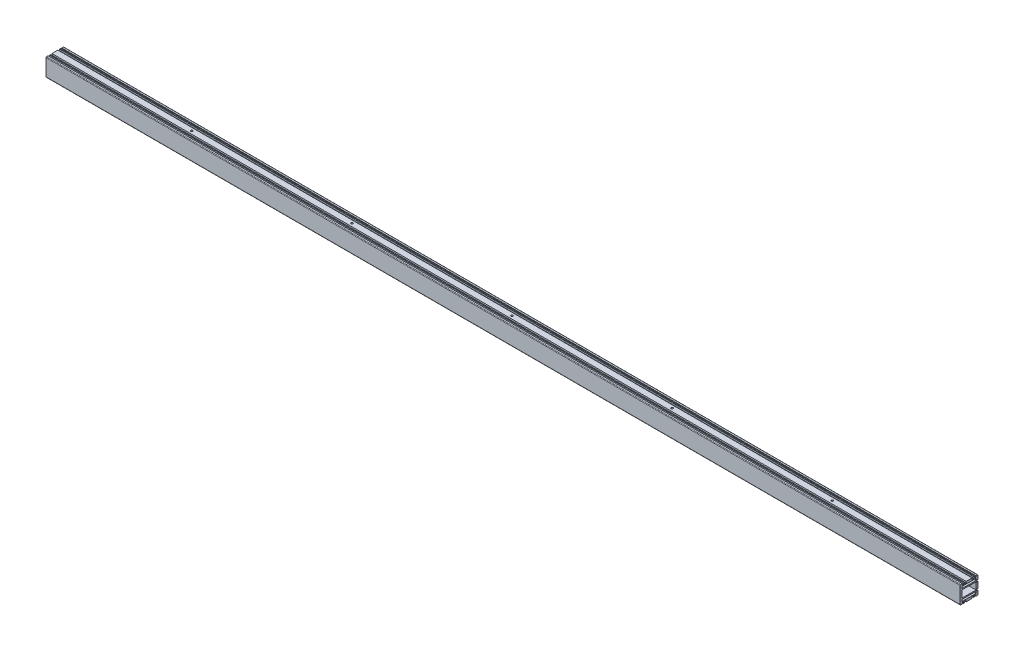
SolidWorks part; units mm, degrees
ref_plane "前视基准面" through (0, 0, 0) normal (0, 0, 1) x (1, 0, 0)
ref_plane "上视基准面" through (0, 0, 0) normal (0, 1, 0) x (1, 0, 0)
ref_plane "右视基准面" through (0, 0, 0) normal (1, 0, 0) x (0, 0, -1)
sketch "草图1" plane through (0, 0, 0) normal (1, 0, 0) x (0, 0, -1)
  line L0 (-15, 15) -> (15, -15) construction
  line L1 (-14, 15) -> (-11.5, 15)
  line L2 (-15, 14) -> (-15, -14)
  line L3 (-14, -15) -> (-11.5, -15)
  line L4 (15, 14) -> (15, 8)
  line L5 (15, 15) -> (-15, -15) construction
  line L6 (-11.5, 15) -> (-11.5, 13.5)
  line L7 (-11.5, 13.5) -> (-11.4, 13.5)
  line L8 (-11, 13.1) -> (-11, 12)
  line L9 (-11, 12) -> (-9.5, 12)
  line L10 (-9.5, 12) -> (-9.5, 15)
  line L11 (-9.5, 15) -> (-8, 15)
  line L12 (-8, 15) -> (-8, 12.5)
  line L13 (-8, 12.5) -> (-5, 12.5)
  line L14 (-5, 12.5) -> (-5, 15)
  line L15 (-5, 15) -> (5, 15)
  line L16 (0, 21.5201) -> (0, -18.309) construction
  line L17 (0, 55) -> (0, -55) construction
  line L18 (5, 12.5) -> (5, 15)
  line L19 (8, 12.5) -> (5, 12.5)
  line L20 (8, 15) -> (8, 12.5)
  line L21 (9.5, 15) -> (8, 15)
  line L22 (9.5, 12) -> (9.5, 15)
  line L23 (11, 12) -> (9.5, 12)
  line L24 (11, 13.1) -> (11, 12)
  line L25 (11.5, 13.5) -> (11.4, 13.5)
  line L26 (11.5, 15) -> (11.5, 13.5)
  line L27 (8, 15) -> (9.5, 15)
  line L28 (11.5, 15) -> (14, 15)
  line L29 (-19.8303, 0) -> (22.13, 0) construction
  line L30 (55, 0) -> (-55, 0) construction
  line L31 (8, -15) -> (9.5, -15)
  line L32 (11.5, -15) -> (11.5, -13.5)
  line L33 (11.5, -13.5) -> (11.4, -13.5)
  line L34 (11, -13.1) -> (11, -12)
  line L35 (11, -12) -> (9.5, -12)
  line L36 (9.5, -12) -> (9.5, -15)
  line L37 (9.5, -15) -> (8, -15)
  line L38 (8, -15) -> (8, -12.5)
  line L39 (8, -12.5) -> (5, -12.5)
  line L40 (5, -12.5) -> (5, -15)
  line L41 (-5, -15) -> (5, -15)
  line L42 (-5, -12.5) -> (-5, -15)
  line L43 (-8, -12.5) -> (-5, -12.5)
  line L44 (-8, -15) -> (-8, -12.5)
  line L45 (-9.5, -15) -> (-8, -15)
  line L46 (-9.5, -12) -> (-9.5, -15)
  line L47 (-11, -12) -> (-9.5, -12)
  line L48 (-11, -13.1) -> (-11, -12)
  line L49 (-11.5, -13.5) -> (-11.4, -13.5)
  line L50 (-11.5, -15) -> (-11.5, -13.5)
  line L51 (-9.5, -15) -> (-8, -15)
  line L52 (-5, -15) -> (5, -15)
  line L53 (8, -15) -> (9.5, -15)
  line L54 (11.5, -15) -> (14, -15)
  line L55 (15, 8) -> (12.5, 8)
  line L56 (12.5, 8) -> (12.5, 5)
  line L57 (12.5, 5) -> (15, 5)
  line L58 (12.5, -5) -> (15, -5)
  line L59 (12.5, -8) -> (12.5, -5)
  line L60 (15, -8) -> (12.5, -8)
  line L61 (15, 5) -> (15, -5)
  line L62 (15, -8) -> (15, -14)
  line L63 (12, -10.5) -> (12, -8.5)
  line L64 (-11.5, 11) -> (11.5, 11)
  line L65 (-12, 10.5) -> (-12, 8.5)
  line L66 (-11.5, 8) -> (11.5, 8)
  line L67 (12, 10.5) -> (12, 8.5)
  line L68 (-11.5, -8) -> (11.5, -8)
  line L69 (-12, -10.5) -> (-12, -8.5)
  line L70 (-11.5, -11) -> (11.5, -11)
  line L72 (-11.75, 6) -> (11.75, 6)
  line L73 (-11.75, 6) -> (-11.75, -6)
  line L74 (-11.75, -6) -> (11.75, -6)
  line L75 (11.75, 6) -> (11.75, -6)
  arc A0 (12, 8.5) -> (11.5, 8) centre (11.5, 8.5) cw
  arc A1 (11.5, 11) -> (12, 10.5) centre (11.5, 10.5) cw
  arc A2 (-11.5, 11) -> (-12, 10.5) centre (-11.5, 10.5) ccw
  arc A3 (-11.5, 8) -> (-12, 8.5) centre (-11.5, 8.5) cw
  arc A4 (-11, -13.1) -> (-11.4, -13.5) centre (-11.4, -13.1) cw
  arc A5 (11.4, -13.5) -> (11, -13.1) centre (11.4, -13.1) cw
  arc A6 (11.4, 13.5) -> (11, 13.1) centre (11.4, 13.1) ccw
  arc A7 (-11, 13.1) -> (-11.4, 13.5) centre (-11.4, 13.1) ccw
  arc A8 (-11.5, -8) -> (-12, -8.5) centre (-11.5, -8.5) ccw
  arc A9 (-11.5, -11) -> (-12, -10.5) centre (-11.5, -10.5) cw
  arc A10 (11.5, -11) -> (12, -10.5) centre (11.5, -10.5) ccw
  arc A11 (12, -8.5) -> (11.5, -8) centre (11.5, -8.5) ccw
  arc A12 (14, 15) -> (15, 14) centre (14, 14) cw
  arc A13 (14, -15) -> (15, -14) centre (14, -14) ccw
  arc A14 (-15, -14) -> (-14, -15) centre (-14, -14) ccw
  arc A15 (-15, 14) -> (-14, 15) centre (-14, 14) cw
  point P69 (12, 11)
  point P72 (-12, 11)
  point P77 (-11, -13.5)
  point P80 (11, -13.5)
  point P83 (11, 13.5)
  point P86 (-11, 13.5)
  point P99 (-12, -11)
  point P100 (12, -11)
  dimension "D17" = 0.5
  dimension "D18" = 0.4
  dimension "D21" = 1
  dimension "D1" = 3.5
  dimension "D2" = 1.5
  dimension "D3" = 0.5
  dimension "D4" = 1.5
  dimension "D5" = 3
  dimension "D6" = 30
  dimension "D7" = 30
  dimension "D8" = 1.5
  dimension "D9" = 2.5
  dimension "D10" = 3
  dimension "D11" = 2.5
  dimension "D12" = 7
  dimension "D13" = 3
  dimension "D14" = 4
  dimension "D15" = 3
  dimension "D16" = 24
  dimension "D19" = 23.5
  dimension "D20" = 12
extrude "凸台-拉伸1" add sketch "草图1" along normal mid plane 1542 contours A15 L2 A14 L3 L50 L49 A4 L48 L47 L46 L45 L44 L43 L42 L41 L40 L39 L38 L31 L36 L35 L34 A5 L33 L32 L54 A13 L62 L60 L59 L58 L61 L57 L56 L55 L4 A12 L28 L26 L25 A6 L24 L23 L22 L21 L20 L19 L18 L15 L14 L13
hole_wizard "M6 螺纹孔1" positions "草图3" profile "草图2" tap size "M6" standard "GB"
sketch "草图3" plane through (0, -15, 0) normal (0, -1, 0) x (1, 0, 0)
  line L0 (-771, -11.5) -> (-771, -14) construction
  line L1 (771, -15) -> (-771, -15) construction
  point P0 (-751, 0)
  point P1 (-736, 0)
  point P4 (736, 0)
  point P7 (751, 0)
  dimension "D1" = 20
  dimension "D2" = 15
sketch "草图2" plane through (-751, -15, 0) normal (1, 0, 0) x (0, 0, -1)
  line L0 (0, 0) -> (0, 16.5022)
  line L1 (0, 16.5022) -> (2.5, 15)
  line L2 (2.5, 15) -> (2.5, 0)
  line L5 (2.5, 0) -> (0, 0)
  line L10 (0, 16.5022) -> (-2.5, 15) construction
  line L11 (0, -6.35) -> (0, 107.95) construction
  dimension "螺纹孔钻头直径" = 5
  dimension "螺纹孔钻头深度" = 15
  dimension "导头角度" = 118
cosmetic thread "孔螺蚊线1" parameters "D1"=9, "D2"=6
cosmetic thread "孔螺蚊线2" parameters "D1"=9, "D2"=6
cosmetic thread "孔螺蚊线3" parameters "D1"=9, "D2"=6
cosmetic thread "孔螺蚊线4" parameters "D1"=9, "D2"=6
hole_wizard "M6 螺纹孔2" positions "草图5" profile "草图4" tap size "M6" standard "GB"
sketch "草图5" plane through (0, 0, -15) normal (0, 0, -1) x (-1, 0, 0)
  line L0 (-771, 5) -> (-771, -5) construction
  line L1 (-771, 15) -> (771, 15) construction
  point P0 (-751, 0)
  point P1 (-736, 0)
  point P4 (736, 0)
  point P7 (751, 0)
  dimension "D1" = 20
  dimension "D2" = 15
sketch "草图4" plane through (751, 0, -15) normal (1, 0, 0) x (0, 1, 0)
  line L0 (0, 0) -> (0, 16.5022)
  line L1 (0, 16.5022) -> (2.5, 15)
  line L2 (2.5, 15) -> (2.5, 0)
  line L5 (2.5, 0) -> (0, 0)
  line L10 (0, 16.5022) -> (-2.5, 15) construction
  line L11 (0, -6.35) -> (0, 107.95) construction
  dimension "螺纹孔钻头直径" = 5
  dimension "螺纹孔钻头深度" = 15
  dimension "导头角度" = 118
cosmetic thread "孔螺蚊线5" parameters "D1"=3.25, "D2"=6
cosmetic thread "孔螺蚊线6" parameters "D1"=3.25, "D2"=6
cosmetic thread "孔螺蚊线7" parameters "D1"=3.25, "D2"=6
cosmetic thread "孔螺蚊线8" parameters "D1"=3.25, "D2"=6
hole_wizard "M4 螺纹孔1" positions "草图7" profile "草图6" tap size "M4" standard "GB"
sketch "草图7" plane through (0, 15, 0) normal (0, 1, 0) x (-1, 0, 0)
  line L0 (-771, 5) -> (-771, -5) construction
  line L1 (-771, 15) -> (771, 15) construction
  point P1 (-540, 0)
  point P3 (-270, 0)
  point P5 (0, 0)
  point P7 (270, 0)
  point P9 (540, 0)
  dimension "D1" = 231
  dimension "D2" = 270
  dimension "D3" = 15
  dimension "D4" = 270
  dimension "D5" = 270
  dimension "D6" = 270
sketch "草图6" plane through (540, 15, 0) normal (1, 0, 0) x (0, 0, 1)
  line L0 (0, 0) -> (0, 11.0914)
  line L1 (0, 11.0914) -> (1.65, 10.1)
  line L2 (1.65, 10.1) -> (1.65, 0)
  line L5 (1.65, 0) -> (0, 0)
  line L10 (0, 11.0914) -> (-1.65, 10.1) construction
  line L11 (0, -6.35) -> (0, 107.95) construction
  dimension "螺纹孔钻头直径" = 3.3
  dimension "螺纹孔钻头深度" = 10.1
  dimension "导头角度" = 118
cosmetic thread "孔螺蚊线9" parameters "D1"=8, "D2"=4
cosmetic thread "孔螺蚊线10" parameters "D1"=8, "D2"=4
cosmetic thread "孔螺蚊线11" parameters "D1"=8, "D2"=4
cosmetic thread "孔螺蚊线12" parameters "D1"=8, "D2"=4
cosmetic thread "孔螺蚊线13" parameters "D1"=8, "D2"=4
hole_wizard "M6 螺纹孔3" positions "草图9" profile "草图8" tap size "M6" standard "GB"
sketch "草图9" plane through (0, 0, -15) normal (0, 0, -1) x (-1, 0, 0)
  line L0 (-771, -15) -> (771, -15) construction
  line L1 (-771, -8) -> (-771, -14) construction
  line L2 (771, -8) -> (771, -14) construction
  point P0 (321, 0)
  point P1 (261, 0)
  point P3 (-261, 0)
  point P5 (-321, 0)
  dimension "D1" = 60
  dimension "D2" = 15
  dimension "D3" = 450
  dimension "D4" = 60
  dimension "D5" = 450
sketch "草图8" plane through (-321, 0, -15) normal (1, 0, 0) x (0, 1, 0)
  line L0 (0, 0) -> (0, 16.5022)
  line L1 (0, 16.5022) -> (2.5, 15)
  line L2 (2.5, 15) -> (2.5, 0)
  line L5 (2.5, 0) -> (0, 0)
  line L10 (0, 16.5022) -> (-2.5, 15) construction
  line L11 (0, -6.35) -> (0, 107.95) construction
  dimension "螺纹孔钻头直径" = 5
  dimension "螺纹孔钻头深度" = 15
  dimension "导头角度" = 118
cosmetic thread "孔螺蚊线14" parameters "D1"=3.25, "D2"=6
cosmetic thread "孔螺蚊线15" parameters "D1"=3.25, "D2"=6
cosmetic thread "孔螺蚊线16" parameters "D1"=3.25, "D2"=6
cosmetic thread "孔螺蚊线17" parameters "D1"=3.25, "D2"=6
